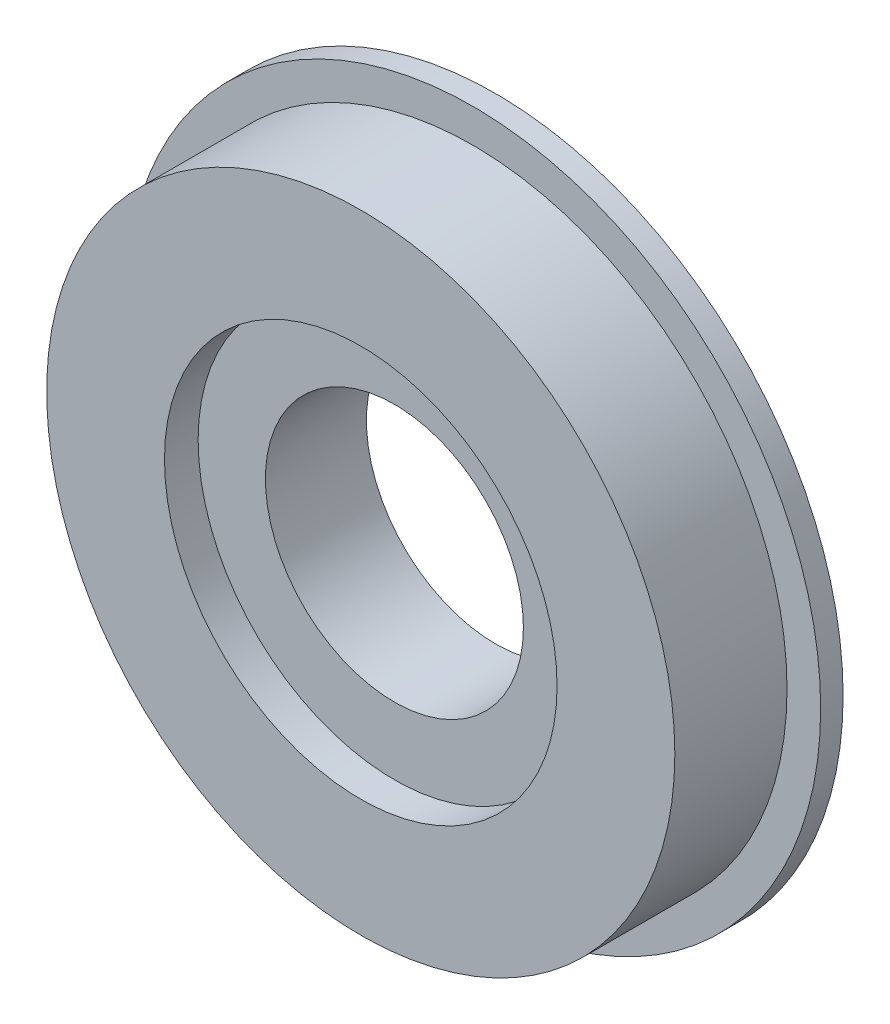
SolidWorks part; units mm, degrees
ref_plane "Alzado" through (0, 0, 0) normal (0, 0, 1) x (1, 0, 0)
ref_plane "Planta" through (0, 0, 0) normal (0, 1, 0) x (1, 0, 0)
ref_plane "Vista lateral" through (0, 0, 0) normal (1, 0, 0) x (0, 0, -1)
sketch "Croquis1" plane through (0, 0, 0) normal (0, 0, 1) x (1, 0, 0)
  circle A0 centre (0, 0) radius 31
extrude "Saliente-Extruir1" add sketch "Croquis1" along normal blind 2
sketch "Croquis2" plane through (0, 0, 2) normal (0, 0, 1) x (1, 0, 0)
  circle A0 centre (0, 0) radius 28
extrude "Saliente-Extruir2" add sketch "Croquis2" along normal blind 10
sketch "Croquis3" plane through (0, 0, 12) normal (0, 0, 1) x (1, 0, 0)
  circle A0 centre (0, 0) radius 11.5
extrude "Cortar-Extruir1" cut sketch "Croquis3" against normal blind 20
sketch "Croquis4" plane through (0, 0, 12) normal (0, 0, 1) x (1, 0, 0)
  circle A1 centre (0, 0) radius 17.5
extrude "Cortar-Extruir2" cut sketch "Croquis4" against normal blind 3
